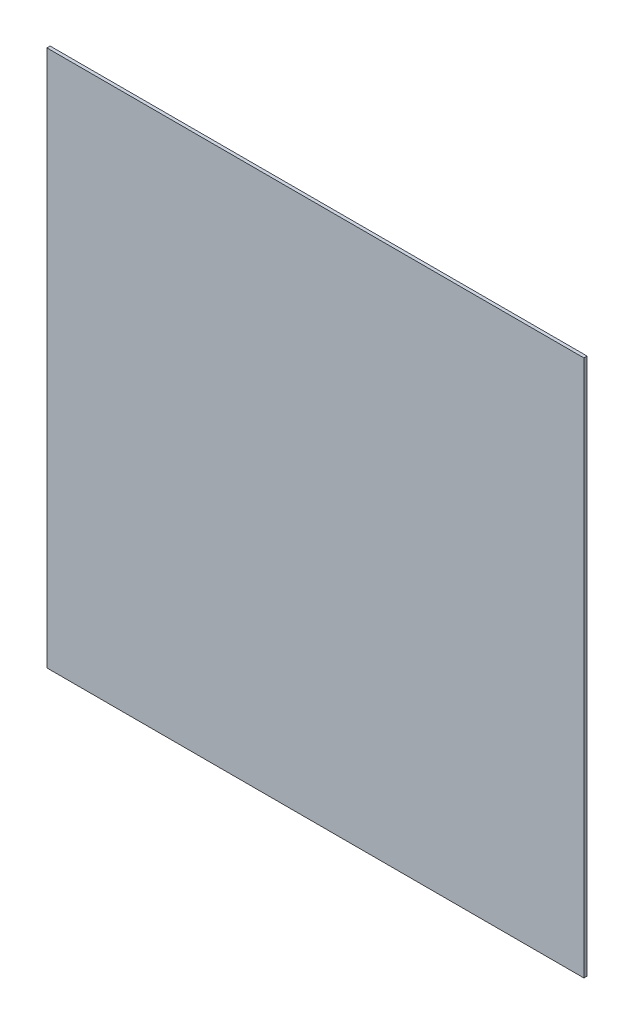
SolidWorks part; units mm, degrees
material "AISI 1035 Steel (SS)"
ref_plane "Front Plane" through (0, 0, 0) normal (0, 0, 1) x (1, 0, 0)
ref_plane "Top Plane" through (0, 0, 0) normal (0, 1, 0) x (1, 0, 0)
ref_plane "Right Plane" through (0, 0, 0) normal (1, 0, 0) x (0, 0, -1)
sketch "Sketch1" plane through (0, 0, 0) normal (0, 0, 1) x (1, 0, 0)
  line L1 (0, 0) -> (127, 0)
  line L2 (0, 0) -> (0, 127)
  line L3 (0, 127) -> (127, 127)
  line L4 (127, 0) -> (127, 127)
  dimension "D1" = 127
  dimension "D2" = 127
extrude "Boss-Extrude1" add sketch "Sketch1" along normal blind 0.762
